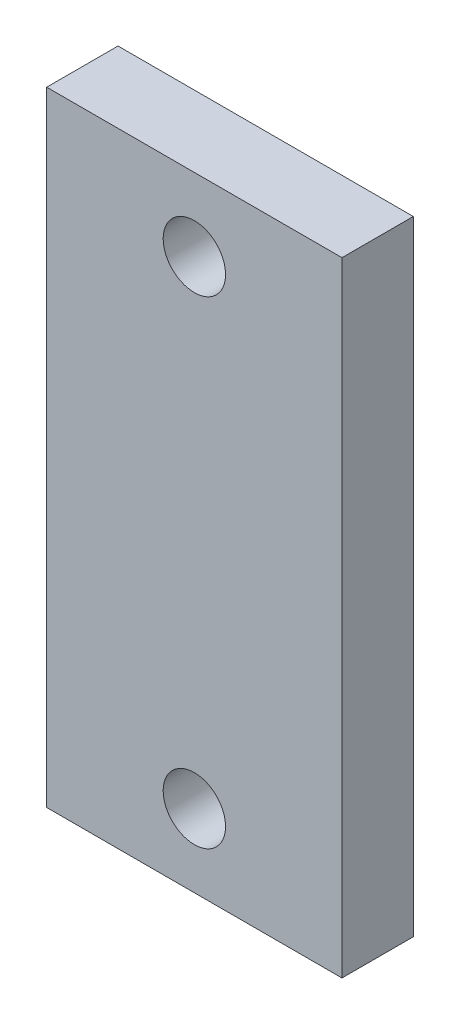
SolidWorks part; units mm, degrees
ref_plane "Alzado" through (0, 0, 0) normal (0, 0, 1) x (1, 0, 0)
ref_plane "Planta" through (0, 0, 0) normal (0, 1, 0) x (1, 0, 0)
ref_plane "Vista lateral" through (0, 0, 0) normal (1, 0, 0) x (0, 0, -1)
sketch "Croquis1" plane through (0, 0, 0) normal (0, 0, 1) x (1, 0, 0)
  line L0 (167.7324, -140.1486) -> (89.7324, -140.1486) construction
  line L1 (89.7324, -110.1486) -> (103.9324, -110.1486)
  line L2 (89.7324, -110.1486) -> (89.7324, -140.1486)
  line L3 (89.7324, -140.1486) -> (103.9324, -140.1486)
  line L4 (103.9324, -110.1486) -> (103.9324, -140.1486)
  circle A0 centre (96.8336, -136.6436) radius 1.5
  circle A1 centre (96.8336, -113.6536) radius 1.5
  dimension "D1" = 103.9324
extrude "Saliente-Extruir1" add sketch "Croquis1" along normal blind 3.43
